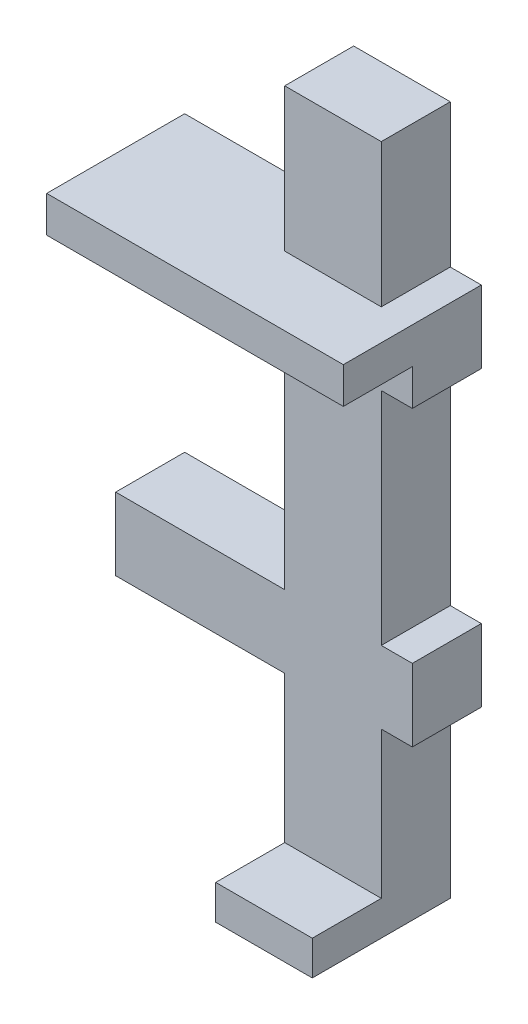
SolidWorks part; units mm, degrees
ref_plane "Front Plane" through (0, 0, 0) normal (0, 0, 1) x (1, 0, 0)
ref_plane "Top Plane" through (0, 0, 0) normal (0, 1, 0) x (1, 0, 0)
ref_plane "Right Plane" through (0, 0, 0) normal (1, 0, 0) x (0, 0, -1)
sketch "Sketch1" plane through (0, 0, 0) normal (0, 0, 1) x (1, 0, 0)
  line L1 (-2.8, -20) -> (2.8, -20)
  line L2 (-2.8, -20) -> (-2.8, 20)
  line L3 (-2.8, 20) -> (2.8, 20)
  line L4 (2.8, -20) -> (2.8, 20)
  line L5 (-2.8, -20) -> (2.8, 20) construction
  line L6 (-2.8, 20) -> (2.8, -20) construction
  point P0 (0, 0)
  dimension "D1" = 40
  dimension "D2" = 5.6
extrude "Boss-Extrude1" add sketch "Sketch1" along normal blind 4 contours L4 L3 L2 L1
sketch "Sketch2" plane through (0, 0, 4) normal (0, 0, 1) x (1, 0, 0)
  line L0 (2.8, -20) -> (2.8, 20) construction
  line L1 (-2.8, -20) -> (2.8, -20)
  line L2 (-2.8, -20) -> (-2.8, -18)
  line L3 (-2.8, -18) -> (2.8, -18)
  line L4 (2.8, -20) -> (2.8, -18)
  dimension "D1" = 2
extrude "Boss-Extrude2" add sketch "Sketch2" along normal blind 4
sketch "Sketch4" plane through (-2.8, 0, 0) normal (-1, 0, 0) x (0, 0, 1)
  line L0 (0, -20) -> (0, 20) construction
  line L1 (0, 11.7) -> (4, 11.7)
  line L2 (0, 11.7) -> (0, 7.5)
  line L3 (0, 7.5) -> (4, 7.5)
  line L4 (4, 11.7) -> (4, 7.5)
  line L5 (4, -18) -> (4, 20) construction
  line L6 (8, -20) -> (0, -20) construction
  dimension "D1" = 4.2
  dimension "D2" = 27.5
extrude "Boss-Extrude3" add sketch "Sketch4" along normal blind 1.8
ref_plane "Plane1" through (0, 0, 0) normal (-1, 0, 0) x (0, 0, 1)
mirror "Mirror1" about plane through (0, 0, 0) normal (-1, 0, 0) of "Boss-Extrude3"
sketch "Sketch6" plane through (0, 0, 4) normal (0, 0, 1) x (1, 0, 0)
  line L0 (2.8, 1.1) -> (-2.8, 1.1) construction
  line L1 (2.8, -18) -> (2.8, 7.5) construction
  line L2 (-2.8, -18) -> (-2.8, 7.5) construction
  line L3 (2.8, -18) -> (-2.8, -18) construction
  line L4 (4.6, 7.5) -> (2.8, 7.5) construction
  dimension "D1" = 19.1
  dimension "D2" = 6.4
sketch "Sketch7" plane through (-2.8, 0, 0) normal (-1, 0, 0) x (0, 0, 1)
  line L0 (4, 1.1) -> (0, 1.1) construction
  line L1 (4, -18) -> (4, 7.5) construction
  line L2 (0, -20) -> (0, 7.5) construction
  line L3 (8, -18) -> (4, -18) construction
  dimension "D1" = 19.1
ref_plane "Plane3" through (0, 1.1, 0) normal (0, -1, 0) x (-1, 0, 0)
mirror "Mirror2" about plane through (0, 1.1, 0) normal (0, -1, 0) of "Mirror1", "Boss-Extrude3"
sketch "Sketch8" plane through (-4.6, 0, 0) normal (-1, 0, 0) x (0, 0, 1)
  line L1 (0, 11.7) -> (4, 11.7)
  line L2 (0, 11.7) -> (0, 7.5)
  line L3 (0, 7.5) -> (4, 7.5)
  line L4 (4, 11.7) -> (4, 7.5)
  line L5 (0, -5.3) -> (4, -5.3)
  line L6 (0, -5.3) -> (0, -9.5)
  line L7 (0, -9.5) -> (4, -9.5)
  line L8 (4, -5.3) -> (4, -9.5)
extrude "Boss-Extrude4" add sketch "Sketch8" along normal blind 8
sketch "Sketch9" plane through (0, 0, 4) normal (0, 0, 1) x (1, 0, 0)
  line L0 (4.6, 7.5) -> (4.6, 11.7) construction
  line L1 (-12.6, 11.7) -> (4.6, 11.7)
  line L2 (-12.6, 11.7) -> (-12.6, 9.6)
  line L3 (-12.6, 9.6) -> (4.6, 9.6)
  line L4 (4.6, 11.7) -> (4.6, 9.6)
extrude "Boss-Extrude5" add sketch "Sketch9" along normal blind 4
